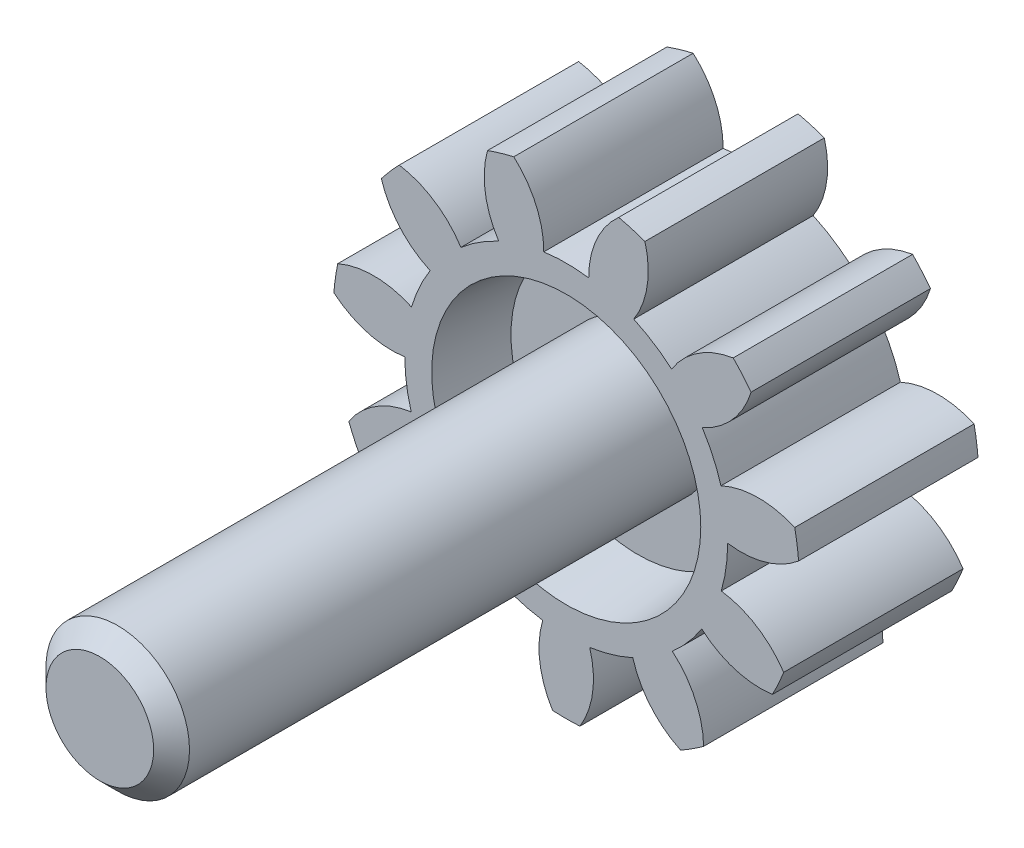
SolidWorks part; units mm, degrees
ref_plane "Спереди" through (0, 0, 0) normal (0, 0, 1) x (1, 0, 0)
ref_plane "Сверху" through (0, 0, 0) normal (0, 1, 0) x (1, 0, 0)
ref_plane "Справа" through (0, 0, 0) normal (1, 0, 0) x (0, 0, -1)
sketch "Эскиз1" plane through (0, 0, 0) normal (0, 0, 1) x (1, 0, 0)
  circle A0 centre (0, 0) radius 13
  dimension "D1" = 26
extrude "Бобышка-Вытянуть1" add sketch "Эскиз1" along normal blind 10 contours A0
sketch "Эскиз2" plane through (0, 0, 10) normal (0, 0, 1) x (1, 0, 0)
  line L0 (0, 0) -> (0, 14.4793) construction
  line L1 (0, 0) -> (-2.0349, 14.4793) construction
  line L2 (0, 0) -> (-3.3416, 14.4742) construction
  arc A0 (1.2526, 8.9124) -> (-1.2526, 8.9124) centre (0, 0) ccw
  arc A1 (-1.2526, 8.9124) -> (0, 9) centre (0, 0) cw
  arc A2 (-1.2526, 8.9124) -> (-2.9244, 12.6668) centre (-6.2525, 8.9354) ccw
  arc A3 (-2.9244, 12.6668) -> (2.9244, 12.6668) centre (0, 0) cw
  arc A4 (1.2526, 8.9124) -> (2.9244, 12.6668) centre (6.2525, 8.9354) cw
  circle A5 centre (0, 0) radius 13 construction
  point P11 (-3.3416, 14.4742)
  point P15 (-2.0349, 14.4742)
  point P16 (0, 14.4793)
  circle M2 centre (0, 0) radius 13
  dimension "18" = 9
  dimension "D4" = 5
  dimension "D1" = 13
  dimension "D2" = 8
extrude "Вырез-Вытянуть1" cut sketch "Эскиз2" against normal blind 10 contours A0 A4 A2 M2
pattern_circular "Круговой массив3" count 11 over 360 about axis through (0, 0, 0) along (0, 0, 1) of "Вырез-Вытянуть1"
sketch "Эскиз3" plane through (0, 0, 10) normal (0, 0, 1) x (1, 0, 0)
  circle A0 centre (0, 0) radius 7.5
  dimension "D1" = 15
extrude "Вырез-Вытянуть2" cut sketch "Эскиз3" against normal blind 4 draft 6
sketch "Эскиз4" plane through (0, 0, 0) normal (0, 0, -1) x (-1, 0, 0)
  circle A0 centre (0, 0) radius 7.5
  dimension "D1" = 15
extrude "Вырез-Вытянуть3" cut sketch "Эскиз4" against normal blind 4 draft 6
sketch "Эскиз5" plane through (0, 0, 6) normal (0, 0, 1) x (1, 0, 0)
  circle A0 centre (0, 0) radius 4
  dimension "D1" = 8
extrude "Бобышка-Вытянуть2" add sketch "Эскиз5" along normal blind 30
chamfer "Фаска1" distance 1 angle 45 1 edges at (4, 0, 36)
